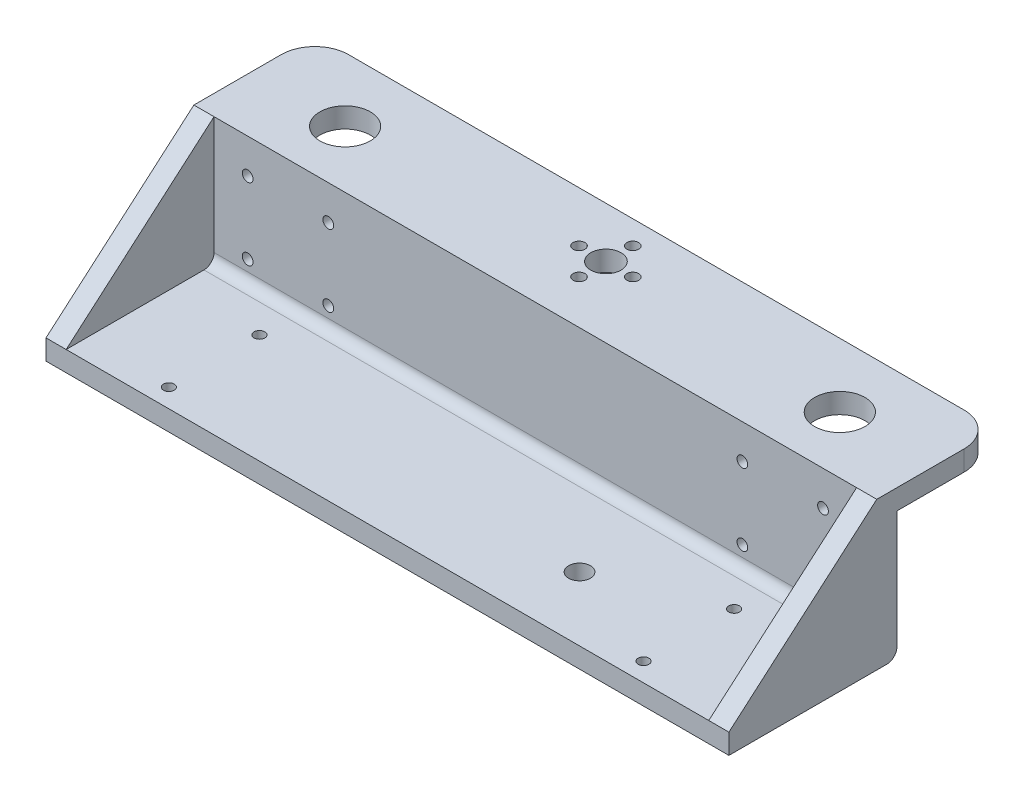
SolidWorks part; units mm, degrees
material "ABS"
ref_plane "Plan de face" through (0, 0, 0) normal (0, 0, 1) x (1, 0, 0)
ref_plane "Plan de dessus" through (0, 0, 0) normal (0, 1, 0) x (1, 0, 0)
ref_plane "Plan de droite" through (0, 0, 0) normal (1, 0, 0) x (0, 0, -1)
sketch "Esquisse1" plane through (0, 0, 0) normal (0, 0, 1) x (1, 0, 0)
  line L1 (-101.6, -16) -> (101.6, -16)
  line L2 (-101.6, -16) -> (-101.6, 16)
  line L3 (-101.6, 16) -> (101.6, 16)
  line L4 (101.6, -16) -> (101.6, 16)
  line L5 (-101.6, -16) -> (101.6, 16) construction
  line L6 (-101.6, 16) -> (101.6, -16) construction
  point P0 (0, 0)
  dimension "D1" = 203.2
  dimension "D2" = 32
extrude "Boss.-Extru.1" add sketch "Esquisse1" along normal blind 6
sketch "Esquisse2" plane through (0, 16, 0) normal (0, 1, 0) x (1, 0, 0)
  line L0 (-101.6, -6) -> (-101.6, 0) construction
  line L1 (101.6, -6) -> (-101.6, -6)
  line L2 (101.6, -6) -> (101.6, 30)
  line L3 (101.6, 30) -> (-101.6, 30)
  line L4 (-101.6, -6) -> (-101.6, 30)
  point P7 (-101.6, -3)
  dimension "D1" = 36
extrude "Boss.-Extru.2" add sketch "Esquisse2" along normal blind 6
sketch "Esquisse3" plane through (0, 22, 0) normal (0, 1, 0) x (1, 0, 0)
  line L0 (-73.6, 11) -> (73.6, 11) construction
  line L1 (101.6, 30) -> (-101.6, 30) construction
  line L3 (-101.6, -6) -> (101.6, -6) construction
  line L4 (0, 15) -> (0, 23) construction
  circle A0 centre (-73.6, 11) radius 7.5
  circle A1 centre (73.6, 11) radius 7.5
  circle A2 centre (0, 15) radius 4.5
  circle A3 centre (0, 15) radius 8 construction
  circle A4 centre (0, 23) radius 1.75
  circle A5 centre (0, 7) radius 1.75
  circle A6 centre (8, 15) radius 1.75
  circle A7 centre (-8, 15) radius 1.75
  point P6 (0, 30)
  point P7 (0, 11)
  dimension "D1" = 15
  dimension "D4" = 9
  dimension "D5" = 16
  dimension "D6" = 3.5
  dimension "D2" = 147.2
  dimension "D3" = 17
  dimension "D7" = 4
extrude "Enlèv. mat.-Extru.1" cut sketch "Esquisse3" against normal through all
sketch "Esquisse6" plane through (0, -16, 0) normal (0, -1, 0) x (1, 0, 0)
  line L1 (101.6, 0) -> (-101.6, 0)
  line L2 (101.6, 0) -> (101.6, 50)
  line L3 (101.6, 50) -> (-101.6, 50)
  line L4 (-101.6, 0) -> (-101.6, 50)
  dimension "D1" = 50
extrude "Boss.-Extru.4" add sketch "Esquisse6" along normal blind 6
sketch "Esquisse7" plane through (101.6, 0, 0) normal (1, 0, 0) x (0, 0, -1)
  line L0 (-50, -16) -> (-6, 22)
  line L1 (-6, 22) -> (0, 22)
  line L2 (-6, 22) -> (30, 22) construction
  line L3 (0, 22) -> (0, -16)
  line L4 (0, -22) -> (0, 16) construction
  line L5 (0, -16) -> (-50, -16)
  line L6 (-6, -16) -> (-6, 22) construction
extrude "Boss.-Extru.5" add sketch "Esquisse7" against normal blind 6
mirror "Symétrie1" about plane through (0, 0, 0) normal (1, 0, 0) of "Boss.-Extru.5"
fillet "Congé3" radius 3 2 edges at (0, -16, 6) (0, -22, 0)
fillet "Congé4" radius 10 2 edges at (101.6, 19, -30) (-101.6, 19, -30)
sketch "Esquisse8" plane through (0, 0, 0) normal (0, 0, -1) x (-1, 0, 0)
  line L0 (-101.6, -19) -> (-101.6, 16) construction
  line L2 (0, 0) -> (0, -19) construction
  line L3 (-101.6, -19) -> (101.6, -19) construction
  line L4 (-91.6, 16) -> (91.6, 16) construction
  point P0 (-85.6, 11.7)
  point P1 (-61.6, 11.7)
  point P2 (-85.6, -9.7)
  point P3 (-61.6, -9.7)
  point P4 (61.6, -9.7)
  point P5 (85.6, -9.7)
  point P6 (61.6, 11.7)
  point P7 (85.6, 11.7)
  dimension "D1" = 21.4
  dimension "D2" = 24
  dimension "D3" = 16
  dimension "D4" = 4.3
hole_wizard "Dégagement M31" positions "Esquisse3D1" profile "Esquisse10" hole size "M3" standard "Ansi Metric"
sketch3d "Esquisse3D1"
  point P0 (85.6, 11.7, 0)
  point P3 (61.6, 11.7, 0)
  point P6 (85.6, -9.7, 0)
  point P9 (61.6, -9.7, 0)
  point P12 (-61.6, 11.7, 0)
  point P15 (-85.6, 11.7, 0)
  point P18 (-61.6, -9.7, 0)
  point P21 (-85.6, -9.7, 0)
sketch "Esquisse10" plane through (85.6, 11.7, 0) normal (1, 0, 0) x (0, 1, 0)
  line L0 (0, 0) -> (0, 6.9614)
  line L1 (0, 6.9614) -> (1.6, 6)
  line L2 (1.6, 6) -> (1.6, 0)
  line L5 (1.6, 0) -> (0, 0)
  line L10 (0, 6.9614) -> (-1.6, 6) construction
  line L11 (0, -6.35) -> (0, 107.95) construction
  dimension "Diamètre du perçage" = 3.2
  dimension "Profondeur du perçage" = 6
  dimension "Angle de pointe" = 118
sketch "Esquisse11" plane through (0, -22, 0) normal (0, -1, 0) x (1, 0, 0)
  line L0 (101.6, 3) -> (101.6, 50) construction
  line L1 (101.6, 50) -> (-101.6, 50) construction
  circle A0 centre (38.1, 30.95) radius 3.2385
  dimension "D3" = 6.477
  dimension "D1" = 63.5
  dimension "D2" = 19.05
extrude "Enlèv. mat.-Extru.3" cut sketch "Esquisse11" against normal blind 6
sketch "Esquisse12" plane through (0, -16, 0) normal (0, 1, 0) x (1, 0, 0)
  line L0 (-70.62, -17.48) -> (70.62, -17.48) construction
  line L1 (-70.62, -44.42) -> (70.62, -44.42) construction
  line L2 (95.6, -50) -> (-95.6, -50) construction
  circle A0 centre (38.1, -30.95) radius 3.2385 construction
  point P0 (-70.62, -44.42)
  point P1 (-70.62, -17.48)
  point P2 (70.62, -44.42)
  point P3 (70.62, -17.48)
  dimension "D3" = 108.72
  dimension "D1" = 26.94
  dimension "D2" = 5.58
  dimension "D4" = 141.24
hole_wizard "Dégagement M32" positions "Esquisse3D2" profile "Esquisse13" hole size "M3" standard "Ansi Metric"
sketch3d "Esquisse3D2"
  point P0 (-70.62, -16, 17.48)
  point P3 (-70.62, -16, 44.42)
  point P6 (70.62, -16, 17.48)
  point P9 (70.62, -16, 44.42)
sketch "Esquisse13" plane through (-70.62, -16, 17.48) normal (1, 0, 0) x (0, 0, 1)
  line L0 (0, 0) -> (0, 6.9614)
  line L1 (0, 6.9614) -> (1.6, 6)
  line L2 (1.6, 6) -> (1.6, 0)
  line L5 (1.6, 0) -> (0, 0)
  line L10 (0, 6.9614) -> (-1.6, 6) construction
  line L11 (0, -6.35) -> (0, 107.95) construction
  dimension "Diamètre du perçage" = 3.2
  dimension "Profondeur du perçage" = 6
  dimension "Angle de pointe" = 118
